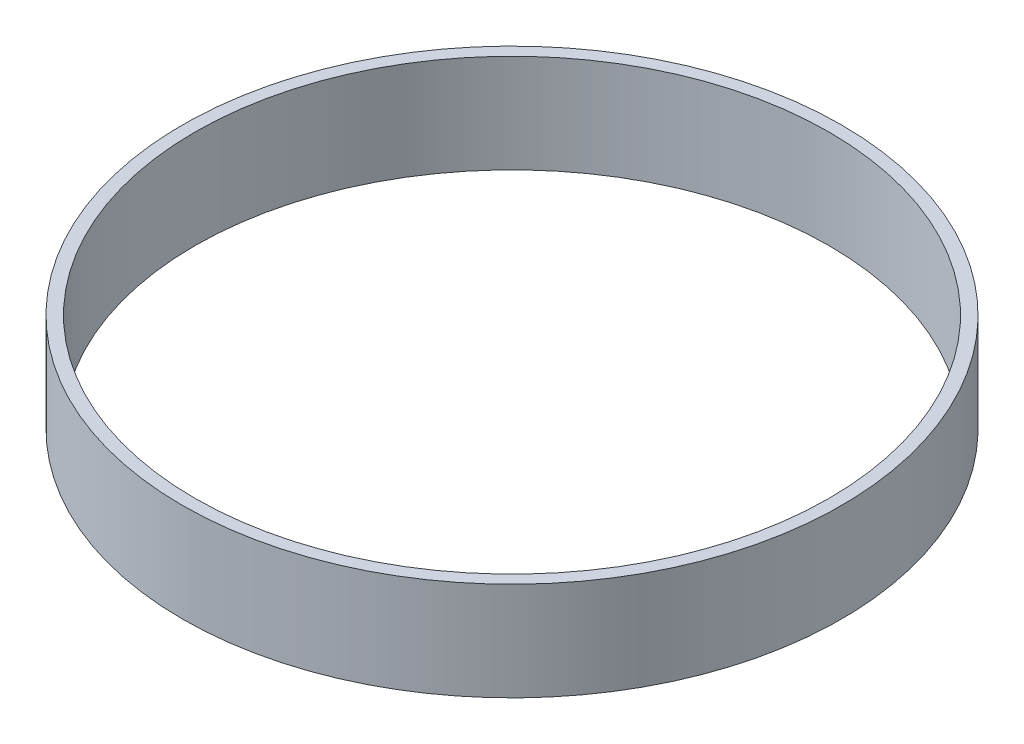
SolidWorks part; units mm, degrees
material "Corrugated Paper"
ref_plane "Front Plane" through (0, 0, 0) normal (0, 0, 1) x (1, 0, 0)
ref_plane "Top Plane" through (0, 0, 0) normal (0, 1, 0) x (1, 0, 0)
ref_plane "Right Plane" through (0, 0, 0) normal (1, 0, 0) x (0, 0, -1)
sketch "Sketch1" plane through (0, 0, 0) normal (0, 0, 1) x (1, 0, 0)
  line L0 (0, 0) -> (0, 22.4918) construction
  line L1 (95.25, 0) -> (91.6634, 0)
  line L2 (95.25, 0) -> (95.25, 28.448)
  line L3 (95.25, 28.448) -> (91.6634, 28.448)
  line L4 (91.6634, 0) -> (91.6634, 28.448)
  dimension "D1" = 28.448
  dimension "D2" = 95.25
  dimension "D4" = 3.5866
revolve "Revolve1" add sketch "Sketch1" angle 360 about L0
